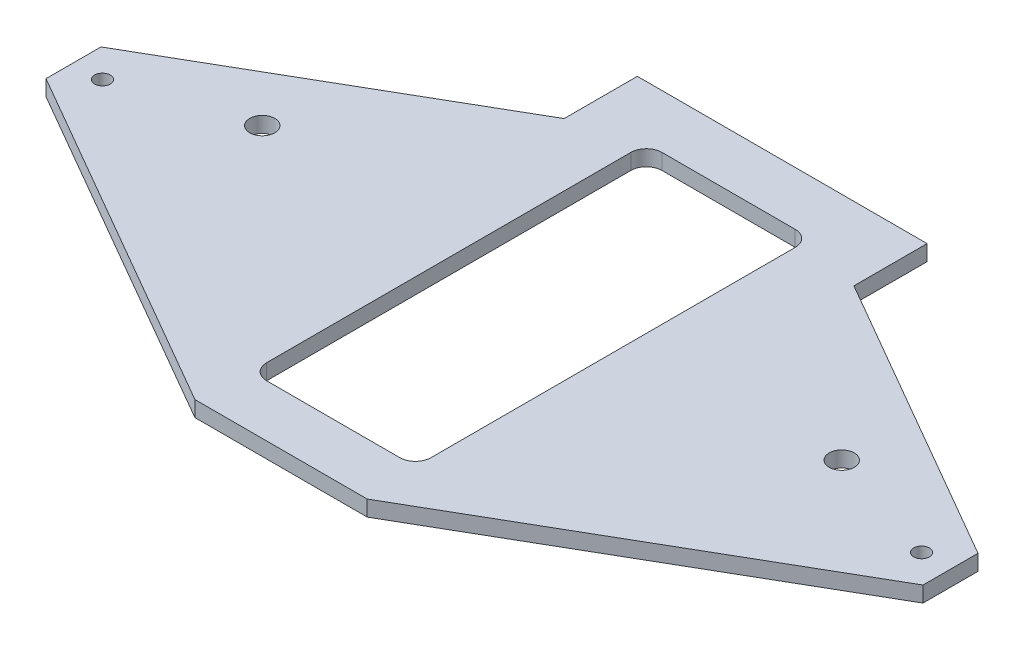
SolidWorks part; units mm, degrees
ref_plane "Front Plane" through (0, 0, 0) normal (0, 0, 1) x (1, 0, 0)
ref_plane "Top Plane" through (0, 0, 0) normal (0, 1, 0) x (1, 0, 0)
ref_plane "Right Plane" through (0, 0, 0) normal (1, 0, 0) x (0, 0, -1)
sketch "Sketch1" plane through (0, 0, 0) normal (0, 1, 0) x (1, 0, 0)
  circle A0 centre (37, 0) radius 1.6 construction
  circle A1 centre (-37, 0) radius 1.6 construction
  circle A2 centre (37, 0) radius 1.6
  circle A3 centre (-37, 0) radius 1.6
sketch "Sketch2" plane through (0, 0, 0) normal (0, 1, 0) x (1, 0, 0)
  line L0 (-18.5, 29.4) -> (18.5, 29.4) construction
  line L1 (-11, -34.6) -> (11, -34.6) construction
  line L2 (11, -34.6) -> (56, -8.6192)
  line L3 (-56, 29.4) -> (56, 29.4) construction
  line L4 (-56, 29.4) -> (-56, -34.6) construction
  line L5 (-56, -34.6) -> (56, -34.6) construction
  line L6 (56, 29.4) -> (56, -34.6) construction
  line L7 (0, 29.4) -> (0, -34.6) construction
  line L8 (56, -8.6192) -> (56, -1.6)
  line L9 (56, -1.6) -> (18.5, 20.0506)
  line L10 (56, -1.6) -> (-56, -1.6) construction
  line L11 (56, -5.1096) -> (-56, -5.1096) construction
  line L12 (18.5, 20.0506) -> (18.5, 29.4)
  line L13 (18.5, 29.4) -> (-18.5, 29.4)
  line L14 (11, -34.6) -> (-11, -34.6)
  line L15 (-11, -34.6) -> (-56, -8.6192)
  line L16 (-56, -8.6192) -> (-56, -1.6)
  line L17 (-56, -1.6) -> (-18.5, 20.0506)
  line L18 (-18.5, 20.0506) -> (-18.5, 29.4)
  circle A0 centre (37, 0) radius 1.6 construction
  circle A1 centre (-37, 0) radius 1.6 construction
  circle A2 centre (-37, 0) radius 1.6 construction
  circle A3 centre (52.3, -5.1096) radius 1
  circle A4 centre (-52.3, -5.1096) radius 1
  point P2 (0, 29.4)
  point P3 (37, -1.6)
  point P5 (-37, -1.6)
  point P8 (-37, 1.6)
  point P11 (-35.4, 0)
  point P12 (-38.6, 0)
  point P13 (38.6, 0)
  point P14 (37, 1.6)
  point P15 (35.4, 0)
  point P18 (0, -34.6)
  point P34 (53.3, -5.1096)
  point P40 (0, -34.6)
  dimension "D8" = 2
  dimension "D1" = 31
  dimension "D2" = 64
  dimension "D3" = 112
  dimension "D4" = 22
  dimension "D5" = 30
  dimension "D6" = 30
  dimension "D7" = 37
  dimension "D9" = 2.7
sketch "Sketch4" plane through (0, 0, 0) normal (0, 1, 0) x (1, 0, 0)
  line L0 (10.5, 20.556) -> (10.5, -25.944) construction
  line L1 (-8.5, 22.556) -> (8.5, 22.556) construction
  line L2 (-10.5, -25.944) -> (-10.5, 20.556) construction
  line L3 (8.5, -27.944) -> (-8.5, -27.944) construction
  line L4 (8.5, -27.944) -> (-8.5, -27.944)
  line L5 (-10.5, -25.944) -> (-10.5, 20.556)
  line L6 (-8.5, 22.556) -> (8.5, 22.556)
  line L7 (10.5, 20.556) -> (10.5, -25.944)
  line L10 (-56, -1.6) -> (-56, -8.6192)
  line L11 (-18.5, 20.0506) -> (-56, -1.6)
  line L12 (-18.5, 29.4) -> (-18.5, 20.0506)
  line L13 (18.5, 29.4) -> (-18.5, 29.4)
  line L14 (18.5, 20.0506) -> (18.5, 29.4)
  line L15 (56, -1.6) -> (18.5, 20.0506)
  line L16 (56, -8.6192) -> (56, -1.6)
  line L17 (11, -34.6) -> (56, -8.6192)
  line L18 (-11, -34.6) -> (11, -34.6)
  line L19 (-56, -8.6192) -> (-11, -34.6)
  line L20 (-56, -1.6) -> (-56, -8.6192)
  line L21 (-18.5, 20.0506) -> (-56, -1.6)
  line L22 (-18.5, 29.4) -> (-18.5, 20.0506)
  line L23 (18.5, 29.4) -> (-18.5, 29.4)
  line L24 (18.5, 20.0506) -> (18.5, 29.4)
  line L25 (56, -1.6) -> (18.5, 20.0506)
  line L26 (56, -8.6192) -> (56, -1.6)
  line L27 (11, -34.6) -> (56, -8.6192)
  line L28 (-11, -34.6) -> (11, -34.6)
  line L29 (-56, -8.6192) -> (-11, -34.6)
  circle A0 centre (37, 0) radius 1.6 construction
  circle A1 centre (-52.3, -5.1096) radius 1
  circle A2 centre (-52.3, -5.1096) radius 1
  circle A3 centre (52.3, -5.1096) radius 1
  circle A4 centre (52.3, -5.1096) radius 1
  circle A5 centre (-37, 0) radius 1.6 construction
  circle A6 centre (37, 0) radius 1.6
  circle A7 centre (-37, 0) radius 1.6
  arc A8 (-8.5, 22.556) -> (-10.5, 20.556) centre (-8.5, 20.556) ccw construction
  arc A9 (10.5, 20.556) -> (8.5, 22.556) centre (8.5, 20.556) ccw construction
  arc A10 (8.5, -27.944) -> (10.5, -25.944) centre (8.5, -25.944) ccw construction
  arc A11 (-10.5, -25.944) -> (-8.5, -27.944) centre (-8.5, -25.944) ccw construction
  arc A12 (8.5, -27.944) -> (10.5, -25.944) centre (8.5, -25.944) ccw
  arc A13 (-10.5, -25.944) -> (-8.5, -27.944) centre (-8.5, -25.944) ccw
  arc A14 (-8.5, 22.556) -> (-10.5, 20.556) centre (-8.5, 20.556) ccw
  arc A15 (10.5, 20.556) -> (8.5, 22.556) centre (8.5, 20.556) ccw
  dimension "D1" = 0
  dimension "D2" = 0
  dimension "D3" = 0
extrude "Boss-Extrude1" add sketch "Sketch4" against normal blind 2
